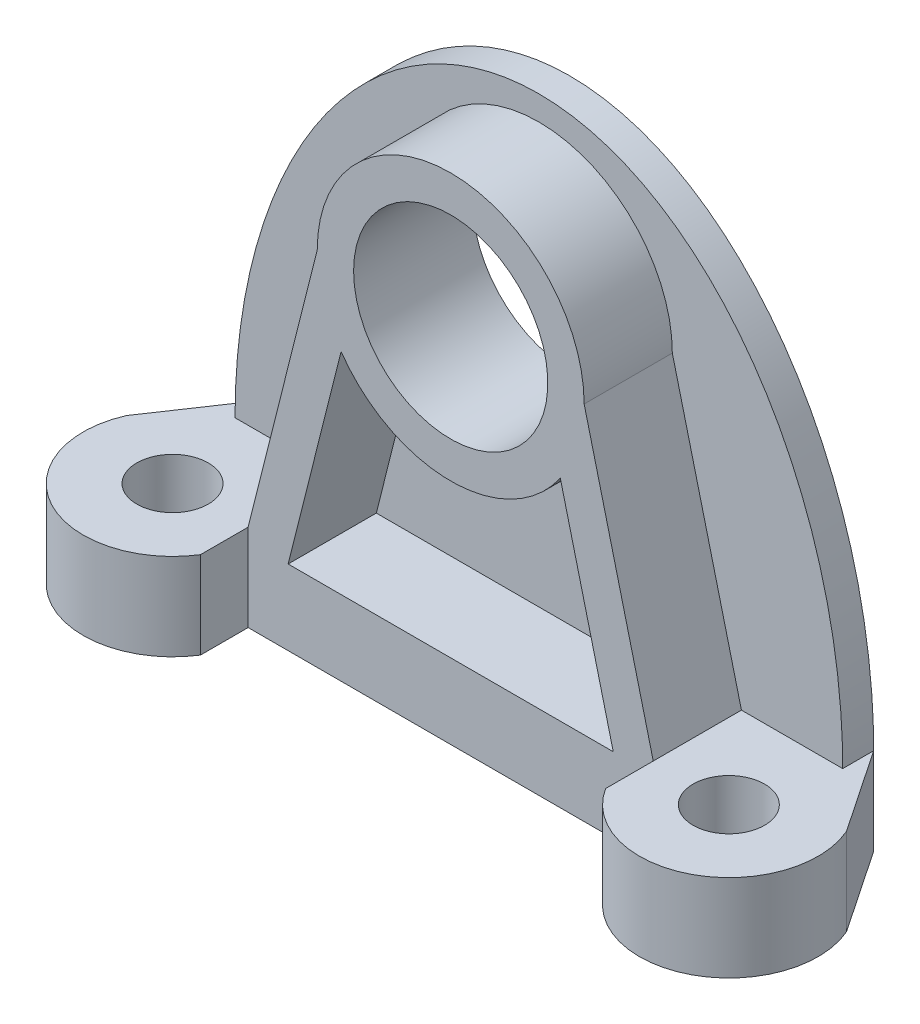
SolidWorks part; units mm, degrees
ref_plane "Alzado" through (0, 0, 0) normal (0, 0, 1) x (1, 0, 0)
ref_plane "Planta" through (0, 0, 0) normal (0, 1, 0) x (1, 0, 0)
ref_plane "Vista lateral" through (0, 0, 0) normal (1, 0, 0) x (0, 0, -1)
sketch "Croquis2" plane through (0, 0, 0) normal (0, 1, 0) x (1, 0, 0)
  line L0 (-25.5, 0) -> (25.5, 0)
  line L1 (25.5, 0) -> (30.2182, -7)
  line L2 (17, -14) -> (17, -10)
  line L3 (17, -10) -> (-17, -10)
  line L4 (0, 0) -> (0, -10) construction
  line L5 (30.2182, -7) -> (0, -7) construction
  line L6 (-17, -14) -> (-17, -10)
  line L7 (-25.5, 0) -> (-30.2182, -7)
  arc A0 (30.2182, -7) -> (17, -14) centre (23.3443, -10) cw
  circle A1 centre (23.3443, -10) radius 3
  circle A2 centre (-23.3443, -10) radius 3
  arc A3 (-30.2182, -7) -> (-17, -14) centre (-23.3443, -10) ccw
  dimension "D2" = 7.5
  dimension "D6" = 6
  dimension "D1" = 17
  dimension "D3" = 25.5
  dimension "D4" = 10
  dimension "D5" = 4
  dimension "D7" = 3
extrude "Saliente-Extruir1" add sketch "Croquis2" along normal blind 7.3
sketch "Croquis3" plane through (0, 0, 10) normal (0, 0, 1) x (1, 0, 0)
  line L0 (17, 7.3) -> (17, 0) construction
  line L1 (-17, 7.3) -> (17, 7.3)
  line L2 (-17, 7.3) -> (-17, 6.3)
  line L3 (-17, 6.3) -> (17, 6.3)
  line L4 (17, 7.3) -> (17, 6.3)
  dimension "D1" = 1
extrude "Cortar-Extruir1" cut sketch "Croquis3" against normal blind 7.4
sketch "Croquis5" plane through (0, 0, 0) normal (0, 0, -1) x (-1, 0, 0)
  line L0 (-25.5, 7.3) -> (25.5, 7.3) construction
  line L1 (-25.5, 7.3) -> (25.5, 7.3)
  circle A0 centre (0, 30.35) radius 8.15
  ellipse E0 centre (0, 7.3) end of major axis (0, -29) minor radius 25.5 (-25.5, 7.3) -> (25.5, 7.3) cw
  dimension "D2" = 16.3
  dimension "D1" = 43.6
  dimension "D3" = 13.25
extrude "Saliente-Extruir3" add sketch "Croquis5" against normal up to surface (2.6 mm away) up to face at (0, 6.8, 2.6)
sketch "Croquis6" plane through (0, 0, 2.6) normal (0, 0, 1) x (1, 0, 0)
  line L0 (17, 6.3) -> (17, 7.3)
  line L1 (17, 7.3) -> (11.2, 30.35)
  line L2 (13.6425, 6.3) -> (9.1987, 23.9606)
  line L3 (-17, 6.3) -> (17, 6.3) construction
  line L4 (-17, 6.3) -> (-17, 7.3)
  line L5 (-17, 7.3) -> (-11.2, 30.35)
  line L6 (-13.6425, 6.3) -> (-9.1987, 23.9606)
  line L7 (-17, 6.3) -> (-13.6425, 6.3)
  line L8 (17, 6.3) -> (13.6425, 6.3)
  circle A0 centre (0, 30.35) radius 8.15
  arc A1 (-9.1987, 23.9606) -> (9.1987, 23.9606) centre (0, 30.35) ccw
  arc A2 (11.2, 30.35) -> (-11.2, 30.35) centre (0, 30.35) ccw
  dimension "D1" = 16.3
  dimension "D2" = 22.4
  dimension "D3" = 3.5
  dimension "D4" = 3.5
extrude "Saliente-Extruir4" add sketch "Croquis6" along normal up to surface (7.4 mm away) up to face at (0, 3.15, 10)
